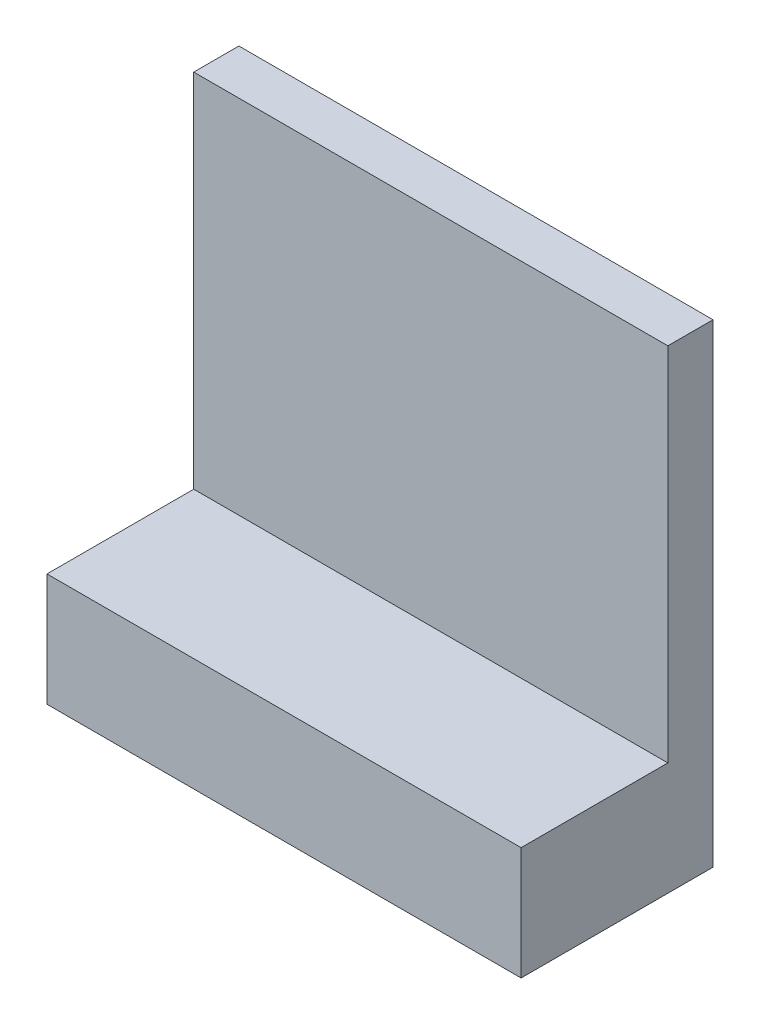
SolidWorks part; units mm, degrees
ref_plane "Ön Düzlem" through (0, 0, 0) normal (0, 0, 1) x (1, 0, 0)
ref_plane "Üst Düzlem" through (0, 0, 0) normal (0, 1, 0) x (1, 0, 0)
ref_plane "Sağ Düzlem" through (0, 0, 0) normal (1, 0, 0) x (0, 0, -1)
sketch "Sketch1" plane through (0, 0, 0) normal (0, 0, 1) x (1, 0, 0)
  line L1 (-21, -21) -> (21, -21)
  line L2 (-21, -21) -> (-21, 21)
  line L3 (-21, 21) -> (21, 21)
  line L4 (21, -21) -> (21, 21)
  line L5 (-21, -21) -> (21, 21) construction
  line L6 (-21, 21) -> (21, -21) construction
  point P0 (0, 0)
  dimension "D1" = 42
extrude "Boss-Extrude1" add sketch "Sketch1" along normal blind 17
sketch "Sketch2" plane through (0, 0, 17) normal (0, 0, 1) x (1, 0, 0)
  line L0 (21, -21) -> (21, 21) construction
  line L1 (-21, 21) -> (21, 21)
  line L2 (-21, 21) -> (-21, -11)
  line L3 (-21, -11) -> (21, -11)
  line L4 (21, 21) -> (21, -11)
  line L5 (-21, -21) -> (21, -21) construction
  dimension "D1" = 10
extrude "Cut-Extrude1" cut sketch "Sketch2" against normal blind 13
